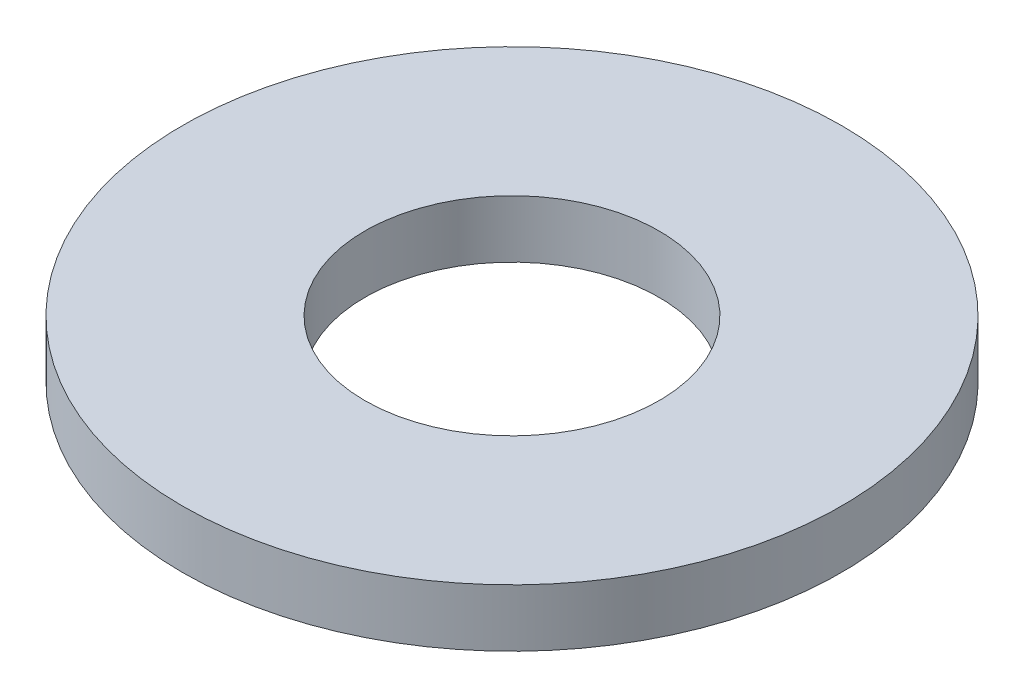
SolidWorks part; units mm, degrees
material "Natural Rubber"
ref_plane "Front Plane" through (0, 0, 0) normal (0, 0, 1) x (1, 0, 0)
ref_plane "Top Plane" through (0, 0, 0) normal (0, 1, 0) x (1, 0, 0)
ref_plane "Right Plane" through (0, 0, 0) normal (1, 0, 0) x (0, 0, -1)
sketch "Main Sketch" plane through (0, 0, 0) normal (0, 1, 0) x (1, 0, 0)
  circle A0 centre (0, 0) radius 12.425
  circle A1 centre (0, 0) radius 5.545
  dimension "D1" = 24.85
  dimension "D2" = 6.88
extrude "O-Ring Extrude" add sketch "Main Sketch" along normal mid plane 2.17
